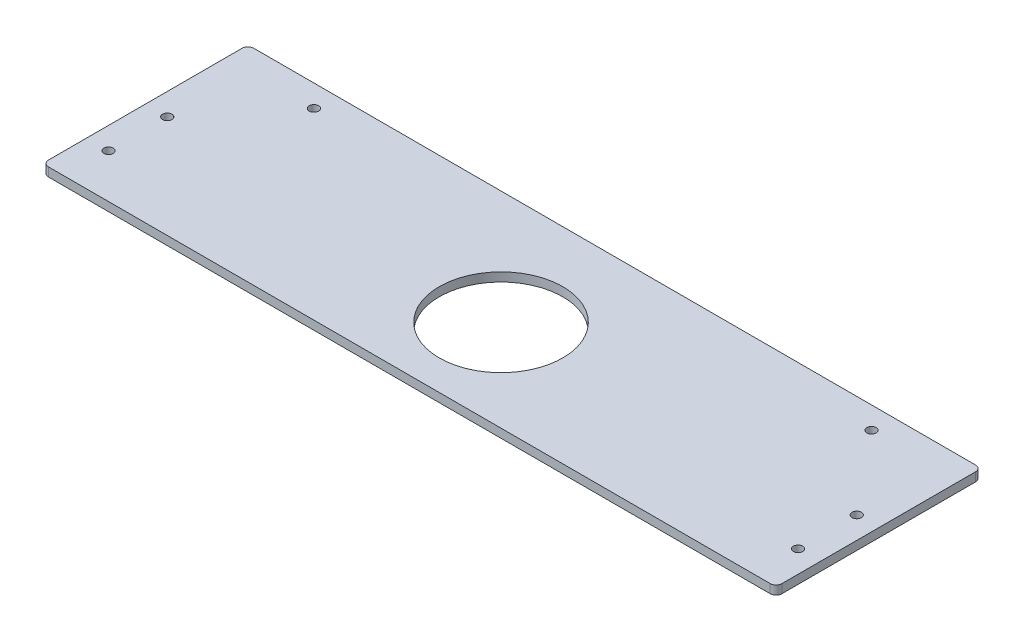
SolidWorks part; units mm, degrees
material "Thornel Mat VMA"
ref_plane "前视基准面" through (0, 0, 0) normal (0, 0, 1) x (1, 0, 0)
ref_plane "上视基准面" through (0, 0, 0) normal (0, 1, 0) x (1, 0, 0)
ref_plane "右视基准面" through (0, 0, 0) normal (1, 0, 0) x (0, 0, -1)
other "Configuration Table"
sketch "草图1" plane through (0, 0, 0) normal (0, 1, 0) x (1, 0, 0)
  line L1 (-125, -35) -> (125, -35)
  line L2 (-125, -35) -> (-125, 35)
  line L3 (-125, 35) -> (125, 35)
  line L4 (125, -35) -> (125, 35)
  line L5 (-125, -35) -> (125, 35) construction
  line L6 (-125, 35) -> (125, -35) construction
  point P0 (0, 0)
  dimension "D1" = 70
  dimension "D2" = 250
extrude "凸台-拉伸1" add sketch "草图1" along normal blind 3
sketch "草图2" plane through (0, 3, 0) normal (0, 1, 0) x (1, 0, 0)
  line L0 (-117.5, 35) -> (-117.5, -35) construction
  line L1 (125, 35) -> (-125, 35) construction
  line L2 (-125, -35) -> (125, -35) construction
  line L3 (-125, 27.5) -> (125, 27.5) construction
  line L4 (-125, 35) -> (-125, -35) construction
  line L5 (125, -35) -> (125, 35) construction
  line L6 (0, 0) -> (0, -35) construction
  circle A0 centre (-95, 27.5) radius 1.6
  circle A1 centre (95, 27.5) radius 1.6
  circle A2 centre (-117.5, 0) radius 1.6
  circle A3 centre (-117.5, -20) radius 1.6
  circle A4 centre (117.5, -20) radius 1.6
  circle A5 centre (117.5, 0) radius 1.6
  dimension "D3" = 3.2
  dimension "D4" = 3.2
  dimension "D5" = 3.2
  dimension "D6" = 3.2
  dimension "D7" = 30
  dimension "D8" = 30
  dimension "D9" = 35
  dimension "D10" = 20
  dimension "D1" = 7.5
  dimension "D2" = 7.5
extrude "切除-拉伸1" cut sketch "草图2" against normal through all
fillet "圆角2" radius 2 4 edges at (125, 1.5, 35) (125, 1.5, -35) (-125, 1.5, 35) (-125, 1.5, -35)
sketch "草图3" plane through (0, 3, 0) normal (0, 1, 0) x (1, 0, 0)
  line L0 (0, 35) -> (0, -35) construction
  line L1 (123, 35) -> (-123, 35) construction
  line L2 (-123, -35) -> (123, -35) construction
  circle A0 centre (0, -3.75) radius 21.05
  dimension "D1" = 42.1
  dimension "D2" = 38.75
extrude "切除-拉伸2" cut sketch "草图3" against normal through all
